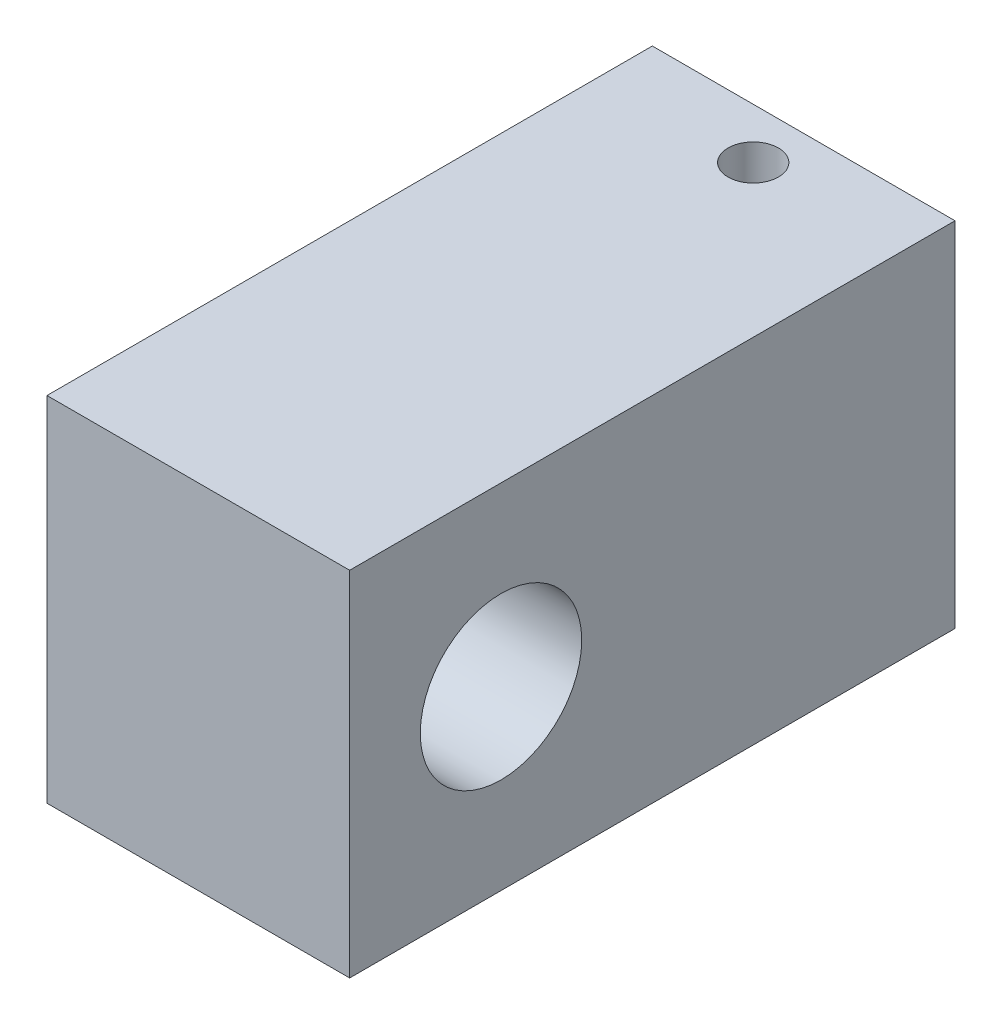
SolidWorks part; units mm, degrees
material "6063-T6"
ref_plane "Front Plane" through (0, 0, 0) normal (0, 0, 1) x (1, 0, 0)
ref_plane "Top Plane" through (0, 0, 0) normal (0, 1, 0) x (1, 0, 0)
ref_plane "Right Plane" through (0, 0, 0) normal (1, 0, 0) x (0, 0, -1)
sketch "Sketch1" plane through (0, 0, 0) normal (0, 0, 1) x (1, 0, 0)
  line L1 (0, 0) -> (30, 0)
  line L2 (0, 0) -> (0, 35)
  line L3 (0, 35) -> (30, 35)
  line L4 (30, 0) -> (30, 35)
  dimension "D1" = 30
  dimension "D2" = 35
extrude "Boss-Extrude1" add sketch "Sketch1" along normal blind 60
sketch "Sketch2" plane through (30, 0, 0) normal (1, 0, 0) x (0, 0, -1)
  line L0 (-60, 0) -> (-60, 35) construction
  line L1 (-60, 35) -> (0, 35) construction
  circle A0 centre (-45, 17.5) radius 8
  dimension "D1" = 16
  dimension "D2" = 15
  dimension "D3" = 17.5
extrude "Cut-Extrude1" cut sketch "Sketch2" against normal through all
sketch "Sketch3" plane through (0, 0, 0) normal (0, 0, -1) x (-1, 0, 0)
  line L0 (-30, 35) -> (0, 35) construction
  line L1 (-30, 0) -> (-30, 35) construction
  circle A0 centre (-15, 17.5) radius 5
  dimension "D1" = 10
  dimension "D2" = 17.5
  dimension "D3" = 15
extrude "Cut-Extrude2" cut sketch "Sketch3" against normal blind 10
sketch "Sketch5" plane through (0, 35, 0) normal (0, 1, 0) x (1, 0, 0)
  line L0 (30, 0) -> (0, 0) construction
  line L1 (0, -60) -> (0, 0) construction
  circle A0 centre (15, -5) radius 2.5
  dimension "D1" = 5
  dimension "D2" = 5
  dimension "D3" = 15
extrude "Cut-Extrude4" cut sketch "Sketch5" against normal blind 15
